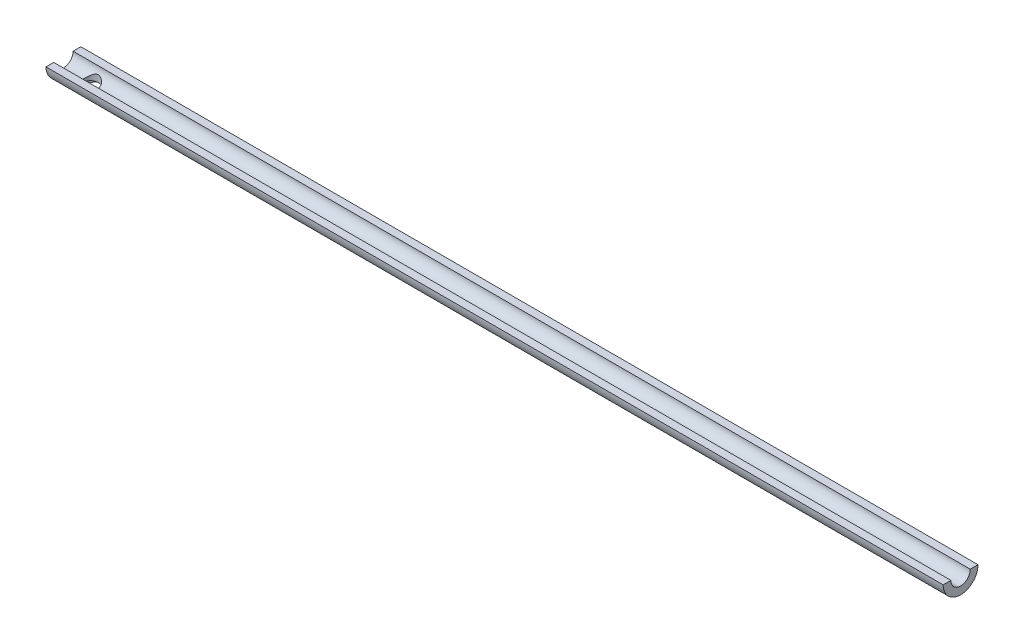
SolidWorks part; units mm, degrees
ref_plane "Front Plane" through (0, 0, 0) normal (0, 0, 1) x (1, 0, 0)
ref_plane "Top Plane" through (0, 0, 0) normal (0, 1, 0) x (1, 0, 0)
ref_plane "Right Plane" through (0, 0, 0) normal (1, 0, 0) x (0, 0, -1)
sketch "Sketch1" plane through (0, 0, 0) normal (0, 1, 0) x (1, 0, 0)
  line L1 (0, 0) -> (735.584, 0)
  line L2 (0, 0) -> (0, 38.1)
  line L3 (0, 38.1) -> (735.584, 38.1)
  line L4 (735.584, 0) -> (735.584, 38.1)
  dimension "D1" = 735.584
  dimension "D2" = 38.1
extrude "wood block" add sketch "Sketch1" along normal blind 15.875
sketch "Sketch2" plane through (735.584, 0, 0) normal (1, 0, 0) x (0, 0, -1)
  line L0 (0, 15.875) -> (38.1, 15.875) construction
  circle A0 centre (19.05, 15.875) radius 7.9375
  dimension "D1" = 15.875
extrude "inner bore" cut sketch "Sketch2" against normal through all
sketch "Sketch3" plane through (0, 0, 0) normal (0, 1, 0) x (1, 0, 0)
  line L0 (0, 19.05) -> (22.225, 19.05) construction
  line L1 (0, 26.9875) -> (0, 11.1125) construction
  circle A0 centre (22.225, 19.05) radius 6.35
  point P3 (15.875, 19.05)
  dimension "D1" = 12.7
  dimension "D2" = 15.875
extrude "mouthpiece through hole" cut sketch "Sketch3" along normal through all
sketch "Sketch5" plane through (0, 0, 0) normal (0, -1, 0) x (1, 0, 0)
  circle A0 centre (22.225, -19.05) radius 8.128
  dimension "D1" = 16.256
extrude "Cut-Extrude3" cut sketch "Sketch5" against normal blind 5.5499
sketch "Sketch6" plane through (0, 0, 0) normal (0, -1, 0) x (1, 0, 0)
  line L0 (719.709, -19.05) -> (735.584, -19.05) construction
  line L1 (735.584, 0) -> (735.584, -38.1) construction
  circle A0 centre (713.359, -19.05) radius 6.35 construction
  circle A1 centre (713.359, -19.05) radius 8.128
  dimension "D1" = 12.7
  dimension "D3" = 16.256
  dimension "D2" = 15.875
extrude "Cut-Extrude4" cut sketch "Sketch6" against normal blind 5.3975
sketch "Sketch4" plane through (0, 0, 0) normal (-1, 0, 0) x (0, 0, 1)
  circle A0 centre (-19.05, 15.875) radius 14.2875
  arc A1 (-26.9875, 15.875) -> (-11.1125, 15.875) centre (-19.05, 15.875) ccw construction
  dimension "D1" = 28.575
extrude "outer diameter" cut sketch "Sketch4" against normal through all flip side to cut
